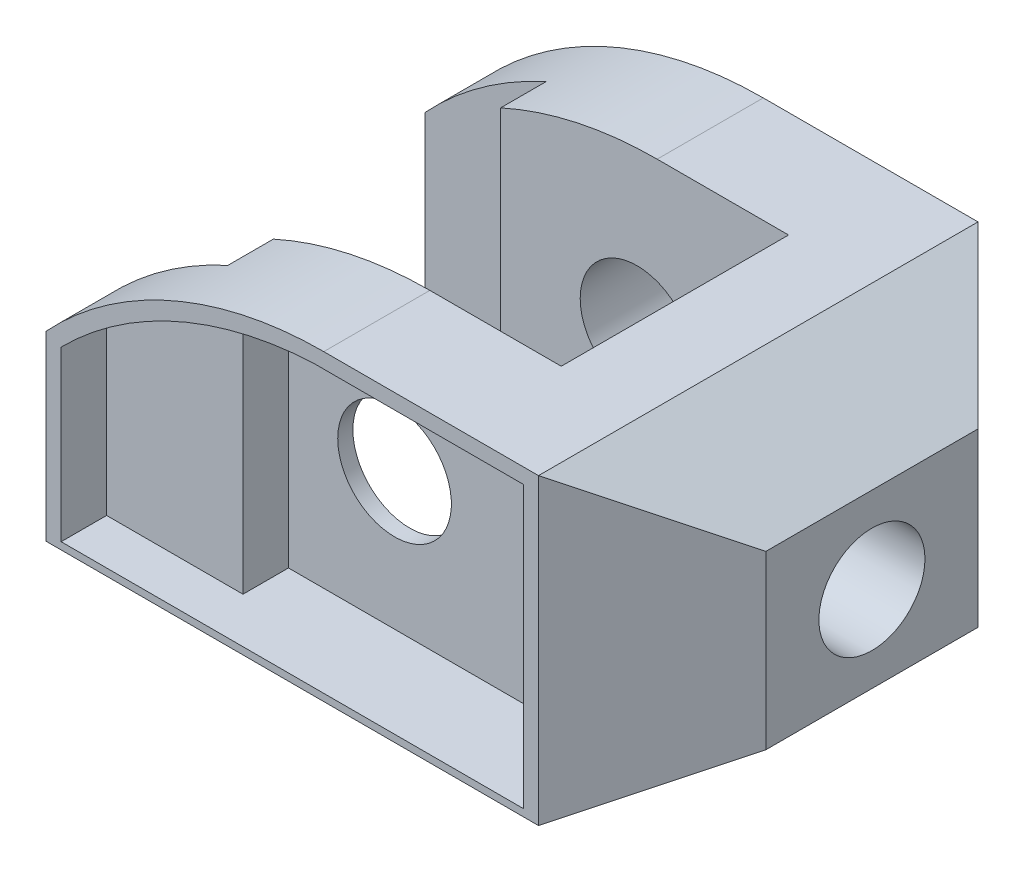
SolidWorks part; units mm, degrees
material "1060 Alloy"
ref_plane "Front Plane" through (0, 0, 0) normal (0, 0, 1) x (1, 0, 0)
ref_plane "Top Plane" through (0, 0, 0) normal (0, 1, 0) x (1, 0, 0)
ref_plane "Right Plane" through (0, 0, 0) normal (1, 0, 0) x (0, 0, -1)
sketch "Sketch3" plane through (0, 0, 0) normal (0, 0, 1) x (1, 0, 0)
  line L0 (0, -42.6875) -> (0, 42.6875) construction
  line L1 (46, 0) -> (-46, 0) construction
  line L2 (-34, 5) -> (-34, -19)
  line L3 (-34, -19) -> (31, -19)
  line L4 (31, -19) -> (46, -10.3397)
  line L5 (46, -10.3397) -> (46, 12.3397)
  line L6 (46, 12.3397) -> (31, 21)
  line L7 (31, 21) -> (2.6606, 21)
  line L8 (31, -19) -> (49.0647, -19) construction
  line L9 (31, 21) -> (46, 21) construction
  circle A0 centre (0, 0) radius 7.5
  arc A1 (-34, 5) -> (2.6606, 21) centre (2.6606, -29) cw
  point P4 (0, 0)
  point P8 (0, 0)
  dimension "D1" = 15
  dimension "D11" = 50
  dimension "D2" = 24
  dimension "D3" = 65
  dimension "D4" = 40
  dimension "D5" = 19
  dimension "D6" = 31
  dimension "D7" = 15
  dimension "D8" = 30
  dimension "D9" = 30
  dimension "D10" = 15
extrude "Boss-Extrude2" add sketch "Sketch3" along normal blind 58
sketch "Sketch5" plane through (0, -19, 0) normal (0, -1, 0) x (1, 0, 0)
  line L0 (46, 29) -> (-38.6388, 29) construction
  line L1 (-34, 58) -> (31, 58) construction
  line L2 (-34, 0) -> (31, 0) construction
  line L3 (-34, 58) -> (-34, 0) construction
  line L4 (-34, 50) -> (-18, 50)
  line L5 (-18, 50) -> (-18, 44)
  line L6 (-18, 44) -> (20, 44)
  line L7 (20, 44) -> (20, 14)
  line L8 (20, 14) -> (-18, 14)
  line L9 (-18, 14) -> (-18, 8)
  line L10 (-18, 8) -> (-34, 8)
  line L12 (31, 58) -> (31, 0) construction
  line L13 (-34, 50) -> (-34, 8)
  dimension "D1" = 29
  dimension "D2" = 8
  dimension "D3" = 16
  dimension "D4" = 6
  dimension "D5" = 11
  dimension "D6" = 8
  dimension "D7" = 16
  dimension "D8" = 6
extrude "Cut-Extrude6" cut sketch "Sketch5" against normal blind 58
sketch "Sketch8" plane through (0, 0, 0) normal (0, 1, 0) x (1, 0, 0)
  line L0 (31, 0) -> (46, 0)
  line L1 (31, 0) -> (46, -15)
  line L2 (46, -58) -> (46, 0) construction
  line L3 (46, -15) -> (46, 0)
  line L4 (46, -58) -> (46, -43)
  line L5 (46, -43) -> (31, -58)
  line L6 (31, -58) -> (46, -58)
  dimension "D1" = 45
  dimension "D2" = 45
extrude "Cut-Extrude9" cut sketch "Sketch8" against normal mid plane 58
sketch "Sketch10" plane through (46, 0, 0) normal (1, 0, 0) x (0, 0, -1)
  line L0 (-29, 12.3397) -> (-29, -10.3397) construction
  line L1 (-43, 12.3397) -> (-15, 12.3397) construction
  line L2 (-43, -10.3397) -> (-15, -10.3397) construction
  line L3 (-43, 1) -> (-15, 1) construction
  line L4 (-43, -10.3397) -> (-43, 12.3397) construction
  line L5 (-15, -10.3397) -> (-15, 12.3397) construction
  circle A0 centre (-29, 1) radius 7
  dimension "D1" = 14
extrude "Cut-Extrude10" cut sketch "Sketch10" against normal mid plane 198
sketch "Sketch11" plane through (0, 0, 58) normal (0, 0, 1) x (1, 0, 0)
  line L0 (29, 19) -> (29, -18.0556)
  line L1 (29, -18.0556) -> (-32, -18.0556)
  line L2 (-32, -18.0556) -> (-32, 4.1908)
  line L3 (1.3243, 19) -> (29, 19)
  line L4 (31, -19) -> (31, 21) construction
  line L5 (-34, 5) -> (-34, -19) construction
  line L6 (31, 21) -> (2.6606, 21) construction
  line L7 (-16, 15.0732) -> (-16, -18.0556)
  arc A0 (-32, 4.1908) -> (1.3243, 19) centre (3.5078, -30.8117) cw
  arc A1 (2.6606, 21) -> (-34, 5) centre (2.6606, -29) ccw construction
  dimension "D5" = 2
  dimension "D6" = 30.8117
  dimension "D7" = 49.8596
  dimension "D1" = 2
  dimension "D2" = 0.9444
  dimension "D3" = 2
  dimension "D4" = 2
  dimension "D8" = 16
extrude "Cut-Extrude11" cut sketch "Sketch11" against normal blind 6 contours L3 L0 L1 L2 A0
sketch "Sketch12" plane through (0, 0, 52) normal (0, 0, 1) x (1, 0, 0)
  line L0 (29, 19) -> (29, -18.0556)
  line L1 (29, -18.0556) -> (-14, -18.0556)
  line L2 (29, -18.0556) -> (-32, -18.0556) construction
  line L3 (-14, -18.0556) -> (-14, 15.8729)
  line L4 (29, 19) -> (1.3243, 19)
  line L5 (-32, -18.0556) -> (-32, 4.1908) construction
  arc A0 (1.3243, 19) -> (-32, 4.1908) centre (3.5078, -30.8117) ccw construction
  arc A1 (-14, 15.8729) -> (1.3243, 19) centre (3.5078, -30.8117) cw
  dimension "D2" = 49.8596
  dimension "D1" = 18
extrude "Cut-Extrude12" cut sketch "Sketch12" against normal blind 6
